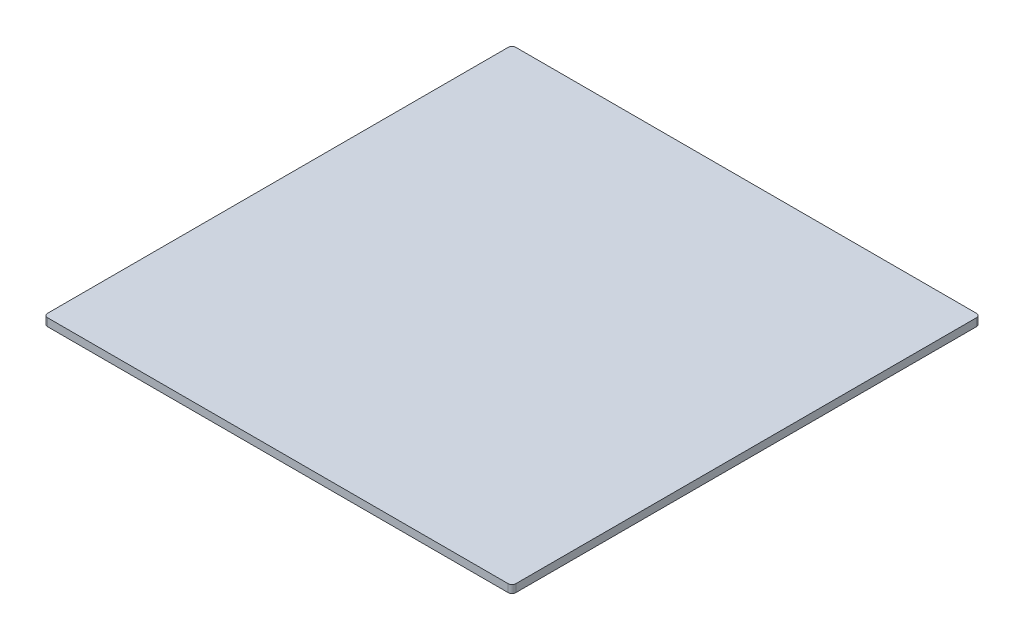
SolidWorks part; units mm, degrees
material "Cobre"
ref_plane "Plano frontal" through (0, 0, 0) normal (0, 0, 1) x (1, 0, 0)
ref_plane "Plano superior" through (0, 0, 0) normal (0, 1, 0) x (1, 0, 0)
ref_plane "Plano direito" through (0, 0, 0) normal (1, 0, 0) x (0, 0, -1)
sketch "Esboço1" plane through (0, 0, 0) normal (0, 1, 0) x (1, 0, 0)
  line L1 (-26.7028, 178.6161) -> (91.2972, 178.6161)
  line L2 (-27.7028, 177.6161) -> (-27.7028, 59.6161)
  line L3 (-26.7028, 58.6161) -> (91.2972, 58.6161)
  line L4 (92.2972, 177.6161) -> (92.2972, 59.6161)
  arc A0 (91.2972, 178.6161) -> (92.2972, 177.6161) centre (91.2972, 177.6161) cw
  arc A1 (91.2972, 58.6161) -> (92.2972, 59.6161) centre (91.2972, 59.6161) ccw
  arc A2 (-27.7028, 59.6161) -> (-26.7028, 58.6161) centre (-26.7028, 59.6161) ccw
  arc A3 (-26.7028, 178.6161) -> (-27.7028, 177.6161) centre (-26.7028, 177.6161) ccw
  dimension "D1" = 1
extrude "Ressalto-extrusão1" add sketch "Esboço1" along normal blind 2
